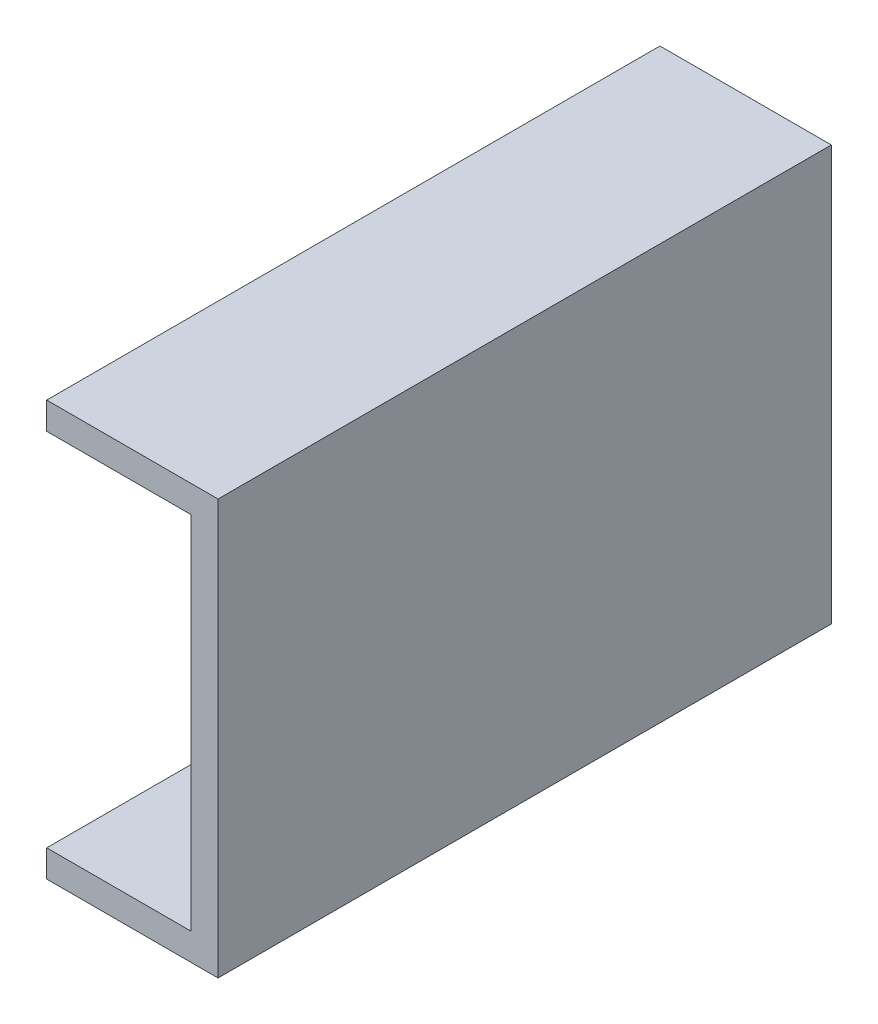
SolidWorks part; units mm, degrees
ref_plane "Front" through (0, 0, 0) normal (0, 0, 1) x (1, 0, 0)
ref_plane "Top" through (0, 0, 0) normal (0, 1, 0) x (1, 0, 0)
ref_plane "Right" through (0, 0, 0) normal (1, 0, 0) x (0, 0, -1)
sketch "草图1" plane through (0, 0, 0) normal (0, 0, 1) x (1, 0, 0)
  line L0 (0, 0) -> (16, 0)
  line L1 (16, 0) -> (16, -40)
  line L2 (16, -40) -> (0, -40)
  line L3 (0, 3) -> (19, 3)
  line L4 (19, 3) -> (19, -43)
  line L5 (19, -43) -> (0, -43)
  line L6 (0, 3) -> (0, 0)
  line L7 (0, -40) -> (0, -43)
  dimension "D1" = 16
  dimension "D2" = 40
  dimension "D3" = 3
extrude "凸台-拉伸1" add sketch "草图1" along normal blind 68
sketch "草图2" plane through (0, -43, 0) normal (0, -1, 0) x (1, 0, 0)
  circle A2 centre (11, 7.2509) radius 2.5
  circle A3 centre (11, 57.2509) radius 2.5
extrude "切除-拉伸1" cut sketch "草图2" against normal blind 10
